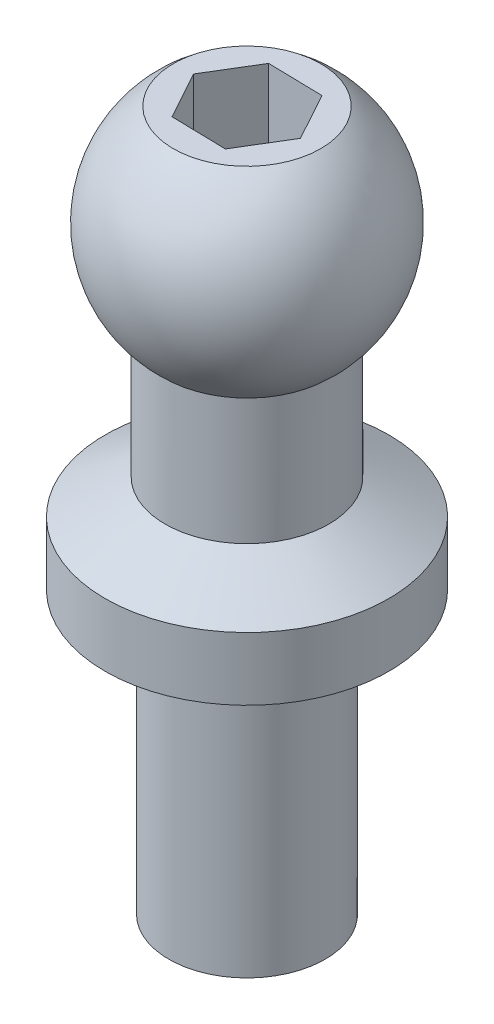
SolidWorks part; units mm, degrees
ref_plane "Piano frontale" through (0, 0, 0) normal (0, 0, 1) x (1, 0, 0)
ref_plane "Piano superiore" through (0, 0, 0) normal (0, 1, 0) x (1, 0, 0)
ref_plane "Piano destro" through (0, 0, 0) normal (1, 0, 0) x (0, 0, -1)
sketch "Schizzo1" plane through (0, 0, 0) normal (0, 0, 1) x (1, 0, 0)
  line L0 (0, 0) -> (0, 11.4819) construction
  line L1 (0, 0) -> (1.24, 0)
  line L2 (1.24, 0) -> (1.24, 4.46)
  line L3 (1.24, 4.46) -> (2.25, 4.46)
  line L4 (2.25, 4.46) -> (2.25, 5.46)
  line L5 (2.25, 5.46) -> (1.3, 6.0085)
  line L6 (1.3, 6.0085) -> (1.3, 8.0085)
  line L7 (0, 0) -> (0, 11.4819)
  arc A0 (1.3, 8.0085) -> (0, 11.4819) centre (0, 9.5019) ccw
  dimension "D7" = 3.96
  dimension "D1" = 2.48
  dimension "D2" = 4.46
  dimension "D3" = 1
  dimension "D4" = 30
  dimension "D5" = 4.5
  dimension "D6" = 2.6
  dimension "D8" = 2
revolve "Rivoluzione1" add sketch "Schizzo1" angle 360 about L0
cosmetic thread "Filettatura cosmetica1" parameters "D2"=2.016
ref_plane "Piano1" through (0, 11.1, 0) normal (0, -1, 0) x (-1, 0, 0)
other "TaglioSuperficie1"
sketch "Schizzo2" plane through (0, 11.1, 0) normal (0, -1, 0) x (-1, 0, 0)
  line L1 (-0.4163, -0.7594) -> (0.4495, -0.7402)
  line L2 (0.4495, -0.7402) -> (0.8658, 0.0191)
  line L3 (0.8658, 0.0191) -> (0.4163, 0.7594)
  line L4 (0.4163, 0.7594) -> (-0.4495, 0.7402)
  line L5 (-0.4495, 0.7402) -> (-0.8658, -0.0191)
  line L6 (-0.8658, -0.0191) -> (-0.4163, -0.7594)
  circle A0 centre (0, 0) radius 0.866 construction
  dimension "D1" = 1.5
extrude "Taglio-Estrusione1" cut sketch "Schizzo2" along normal blind 1.5
